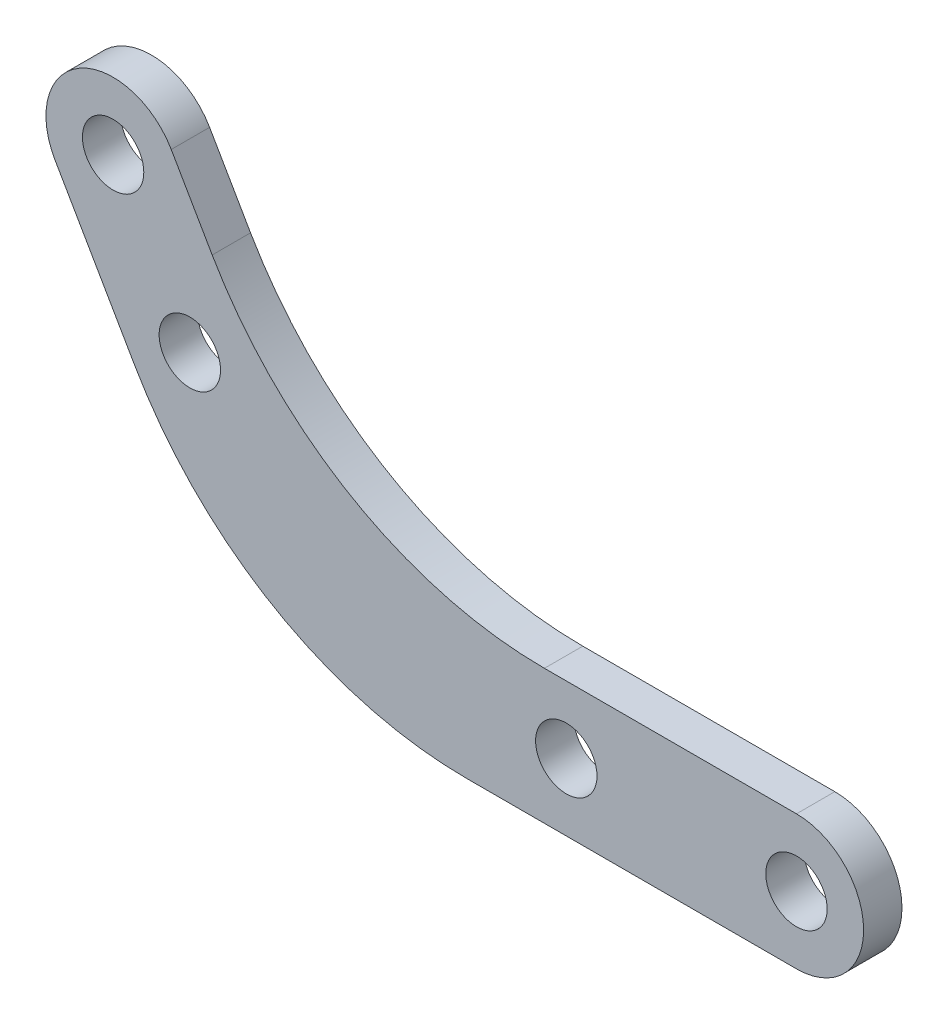
SolidWorks part; units mm, degrees
ref_plane "正面" through (0, 0, 0) normal (0, 0, 1) x (1, 0, 0)
ref_plane "平面" through (0, 0, 0) normal (0, 1, 0) x (1, 0, 0)
ref_plane "右側面" through (0, 0, 0) normal (1, 0, 0) x (0, 0, -1)
sketch "ｽｹｯﾁ1" plane through (0, 0, 0) normal (0, 0, 1) x (1, 0, 0)
  line L0 (0, 0) -> (250, 0) construction
  line L1 (250, 0) -> (300, 86.6025) construction
  line L2 (300, 86.6025) -> (175, 303.1089) construction
  line L3 (175, 303.1089) -> (75, 303.1089) construction
  line L4 (75, 303.1089) -> (-50, 86.6025) construction
  line L5 (-50, 86.6025) -> (0, 0) construction
  line L6 (-17.5, 142.8942) -> (65, 0) construction
  line L7 (185, 0) -> (267.5, 142.8942) construction
  line L8 (42.5, 246.8172) -> (207.5, 246.8172) construction
  line L9 (-9.75, 156.3176) -> (80.5, 0) construction
  line L10 (34.75, 233.3938) -> (215.25, 233.3938) construction
  line L11 (259.75, 156.3176) -> (169.5, 0) construction
  line L12 (75, 35) -> (175, 35) construction
  line L13 (125, 0) -> (125, 35) construction
  line L14 (48.3439, 48.696) -> (58.272, 31.5)
  line L15 (58.272, 31.5) -> (87, 31.5)
  line L16 (54.4061, 52.196) -> (62.3135, 38.5)
  line L17 (62.3135, 38.5) -> (87, 38.5)
  line L18 (87, 38.5) -> (87, 31.5) construction
  line L19 (54.4061, 52.196) -> (48.3439, 48.696) construction
  line L20 (58.4061, 45.2678) -> (52.3439, 41.7678) construction
  line L21 (75, 38.5) -> (75, 31.5) construction
  circle A0 centre (51.375, 50.446) radius 1.6
  circle A1 centre (55.375, 43.5178) radius 1.6
  circle A2 centre (75, 35) radius 1.6
  circle A3 centre (87, 35) radius 1.6
  arc A4 (48.3439, 48.696) -> (54.4061, 52.196) centre (51.375, 50.446) cw
  arc A5 (87, 38.5) -> (87, 31.5) centre (87, 35) cw
  point P19 (35.375, 78.1588)
  point P20 (214.625, 78.1588)
  point P21 (125, 233.3938)
  point P26 (197.625, 48.7139)
  point P27 (193.625, 41.7857)
  dimension "D10" = 8
  dimension "D11" = 32
  dimension "D14" = 3.2
  dimension "D17" = 12
  dimension "D1" = 120
  dimension "D2" = 120
  dimension "D3" = 120
  dimension "D4" = 120
  dimension "D5" = 120
  dimension "D6" = 250
  dimension "D7" = 100
  dimension "D8" = 65
  dimension "D9" = 15.5
  dimension "D12" = 34
  dimension "D13" = 8
  dimension "D15" = 35
  dimension "D16" = 100
  dimension "D18" = 3.5
  dimension "D20" = 7
  dimension "D21" = 7
extrude "ﾎﾞｽ - 押し出し1" add sketch "ｽｹｯﾁ1" along normal blind 2 contours A5 L17 L16 A4 L14 L15 A3 A2 A1 A0
fillet "ﾌｨﾚｯﾄ1" radius 20 2 edges at (62.3135, 38.5, 1) (58.272, 31.5, 1)
